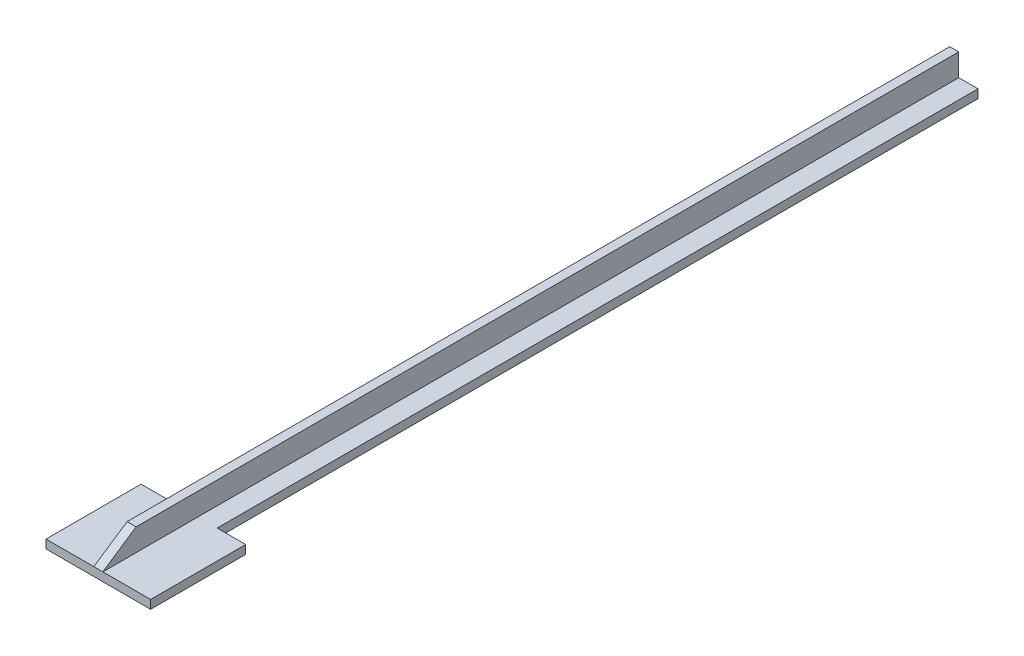
SolidWorks part; units mm, degrees
ref_plane "Front Plane" through (0, 0, 0) normal (0, 0, 1) x (1, 0, 0)
ref_plane "Top Plane" through (0, 0, 0) normal (0, 1, 0) x (1, 0, 0)
ref_plane "Right Plane" through (0, 0, 0) normal (1, 0, 0) x (0, 0, -1)
sketch "Sketch1" plane through (0, 0, 0) normal (0, 0, 1) x (1, 0, 0)
  line L1 (0, 0) -> (10, 0)
  line L2 (0, 0) -> (0, 1.8)
  line L3 (0, 1.8) -> (10, 1.8)
  line L4 (10, 0) -> (10, 1.8)
  line L5 (5.95, 1.8) -> (4.05, 1.8)
  line L6 (5.95, 1.8) -> (5.95, 6.5)
  line L7 (5.95, 6.5) -> (4.05, 6.5)
  line L8 (4.05, 1.8) -> (4.05, 6.5)
  point P9 (5, 6.5)
  point P10 (5, 1.8)
  dimension "D1" = 10
  dimension "D2" = 1.8
  dimension "D3" = 1.9
  dimension "D4" = 6.5
extrude "Boss-Extrude1" add sketch "Sketch1" along normal blind 180 contours L1 L4 L3 L2 | L8 L3 L6 L7
sketch "Sketch2" plane through (0, 0, 180) normal (0, 0, 1) x (1, 0, 0)
  line L0 (0, 0) -> (10, 0) construction
  line L1 (-6, 1.8) -> (16, 1.8)
  line L2 (-6, 1.8) -> (-6, 0)
  line L3 (-6, 0) -> (16, 0)
  line L4 (16, 1.8) -> (16, 0)
  line L5 (0, 1.8) -> (4.05, 1.8) construction
  point P4 (5, 0)
  point P7 (5, 0)
  dimension "D1" = 22
extrude "Boss-Extrude2" add sketch "Sketch2" against normal blind 20
chamfer "Chamfer1" distance 7 distance2 4.7 1 edges at (5, 6.5, 180)
